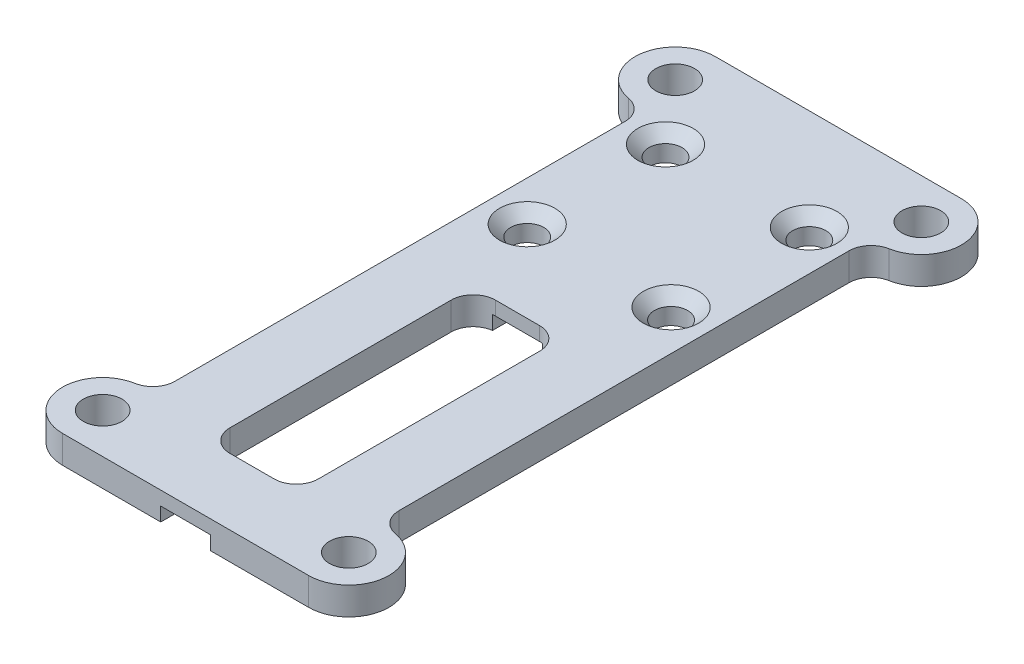
SolidWorks part; units mm, degrees
ref_plane "Front Plane" through (0, 0, 0) normal (0, 0, 1) x (1, 0, 0)
ref_plane "Top Plane" through (0, 0, 0) normal (0, 1, 0) x (1, 0, 0)
ref_plane "Right Plane" through (0, 0, 0) normal (1, 0, 0) x (0, 0, -1)
sketch "Sketch1" plane through (0, 0, 0) normal (0, 1, 0) x (1, 0, 0)
  line L0 (0, 29.5) -> (0, -29.5) construction
  line L1 (-15, 29.5) -> (15, 29.5)
  line L2 (-15, 29.5) -> (-15, -29.5)
  line L3 (-15, -29.5) -> (15, -29.5)
  line L4 (15, 29.5) -> (15, -29.5)
  line L5 (-15, 29.5) -> (15, -29.5) construction
  line L6 (-15, -29.5) -> (15, 29.5) construction
  line L7 (-15, 0) -> (15, 0) construction
  line L8 (0, 29.5) -> (0, -29.5) construction
  line L13 (-10.125, 7.875) -> (-10.125, 22.3907)
  line L14 (-10.125, 7.875) -> (-10.125, -22.3907)
  line L15 (10.125, 7.875) -> (10.125, -22.3907)
  line L16 (10.125, 7.875) -> (10.125, 22.3907)
  circle A0 centre (-11.125, 25.875) radius 1.75
  circle A1 centre (11.125, 25.875) radius 1.75
  circle A2 centre (11.125, -25.875) radius 1.75
  circle A3 centre (-11.125, -25.875) radius 1.75
  circle A4 centre (-6.5, 20.375) radius 1.5
  circle A5 centre (6.5, 20.375) radius 1.5
  circle A6 centre (-6.5, 7.875) radius 1.5
  circle A7 centre (6.5, 7.875) radius 1.5
  circle A8 centre (-6.5, 7.875) radius 3.625
  circle A9 centre (6.5, 7.875) radius 3.625
  circle A10 centre (-11.125, 25.875) radius 3.625
  circle A11 centre (-11.125, -25.875) radius 3.625
  circle A12 centre (11.125, 25.875) radius 3.625
  circle A13 centre (11.125, -25.875) radius 3.625
  point P0 (0, 0)
  dimension "D5" = 3.5
  dimension "D6" = 3
  dimension "D1" = 59
  dimension "D2" = 30
  dimension "D3" = 22.25
  dimension "D4" = 51.75
  dimension "D8" = 18
  dimension "D9" = 12.5
  dimension "D10" = 13
extrude "Boss-Extrude1" add sketch "Sketch1" along normal blind 2.5 contours L3 A13 L15 A9 L16 A12 L1 A10 L13 A8 L14 A11 A5 A4 | A10 A0 | A11 A3 | A13 A2 | A12 A1 | A8 A6 | A9 A7
chamfer "Chamfer1" distance 1 angle 45 4 edges at (-6.5, 2.5, -18.875) (6.5, 2.5, -18.875) (6.5, 2.5, -6.375) (-6.5, 2.5, -6.375)
sketch "Sketch2" plane through (0, 2.5, 0) normal (0, 1, 0) x (1, 0, 0)
  line L0 (0, 29.5) -> (0, -29.5) construction
  line L1 (-11.125, 29.5) -> (11.125, 29.5) construction
  line L2 (-11.125, -29.5) -> (11.125, -29.5) construction
  line L4 (-4, 0.5) -> (4, 0.5)
  line L5 (-4, 0.5) -> (-4, -23.5)
  line L6 (-4, -23.5) -> (4, -23.5)
  line L7 (4, 0.5) -> (4, -23.5)
  line L8 (-4, 0.5) -> (4, -23.5) construction
  line L9 (-4, -23.5) -> (4, 0.5) construction
  point P6 (0, -11.5)
  dimension "D1" = 8
  dimension "D2" = 24
  dimension "D3" = 6
extrude "Cut-Extrude1" cut sketch "Sketch2" against normal up to next
fillet "Fillet1" radius 2 8 edges at (-10.125, 1.25, -22.3907) (-10.125, 1.25, 22.3907) (10.125, 1.25, 22.3907) (10.125, 1.25, -22.3907) (4, 1.25, 23.5) (-4, 1.25, 23.5) (4, 1.25, -0.5) (-4, 1.25, -0.5)
sketch "Sketch3" plane through (0, 0, 0) normal (0, -1, 0) x (1, 0, 0)
  line L0 (-10.125, 0) -> (10.125, 0) construction
  line L1 (-10.125, 20.3396) -> (-10.125, -20.3396) construction
  line L2 (10.125, -20.3396) -> (10.125, 20.3396) construction
  line L3 (-11.125, -29.5) -> (11.125, -29.5) construction
  line L4 (-2.25, 29.5) -> (2.25, 29.5)
  line L5 (-2.25, 29.5) -> (-2.25, -29.5)
  line L6 (-2.25, -29.5) -> (2.25, -29.5)
  line L7 (2.25, 29.5) -> (2.25, -29.5)
  line L8 (-2.25, 29.5) -> (2.25, -29.5) construction
  line L9 (-2.25, -29.5) -> (2.25, 29.5) construction
  point P6 (0, 0)
  dimension "D1" = 4.5
extrude "Cut-Extrude2" cut sketch "Sketch3" against normal blind 1.25
